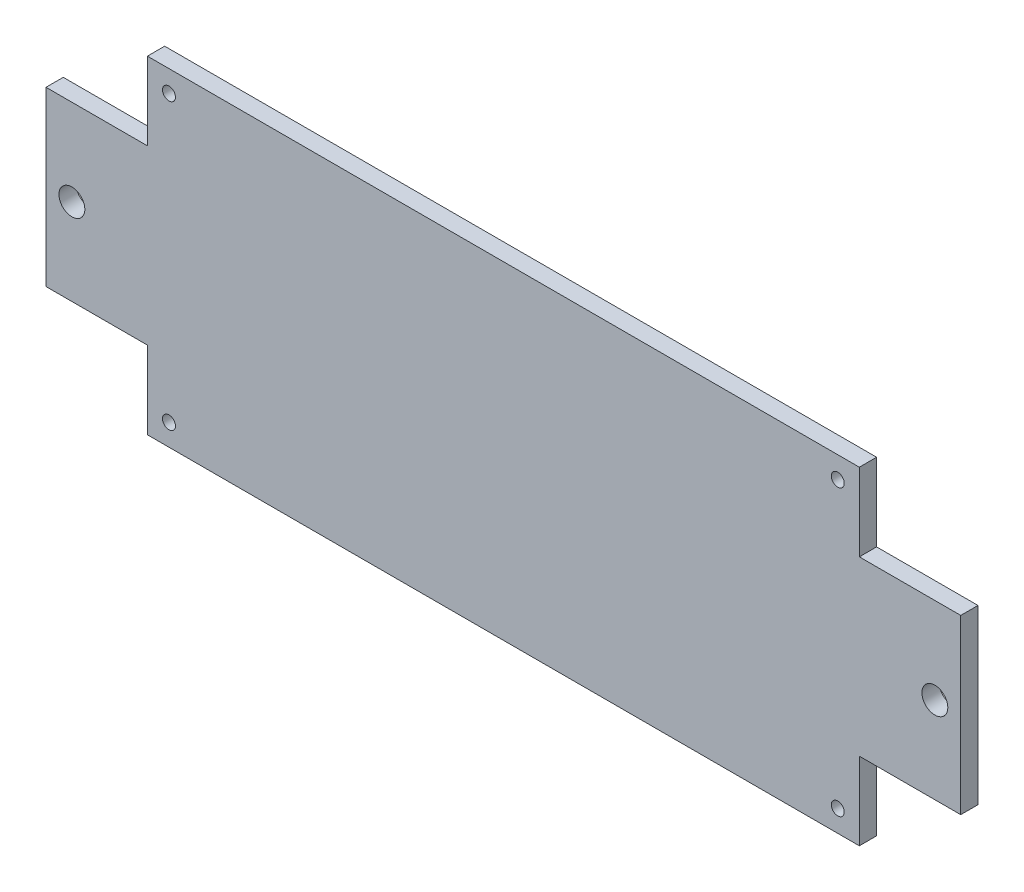
SolidWorks part; units mm, degrees
ref_plane "Front Plane" through (0, 0, 0) normal (0, 0, 1) x (1, 0, 0)
ref_plane "Top Plane" through (0, 0, 0) normal (0, 1, 0) x (1, 0, 0)
ref_plane "Right Plane" through (0, 0, 0) normal (1, 0, 0) x (0, 0, -1)
sketch "Sketch1" plane through (0, 0, 0) normal (0, 0, 1) x (1, 0, 0)
  line L0 (99.0449, 45.8482) -> (99.0449, -30.1518) construction
  line L1 (16.5449, 45.8482) -> (181.5449, 45.8482)
  line L2 (16.5449, 45.8482) -> (16.5449, 27.8482)
  line L3 (16.5449, -30.1518) -> (181.5449, -30.1518)
  line L4 (181.5449, 45.8482) -> (181.5449, 27.8482)
  line L5 (-6.9551, 7.8482) -> (205.0449, 7.8482) construction
  line L6 (181.5449, -12.1518) -> (181.5449, -30.1518)
  line L7 (181.5449, 27.8482) -> (205.0449, 27.8482)
  line L9 (181.5449, -12.1518) -> (205.0449, -12.1518)
  line L10 (205.0449, 27.8482) -> (205.0449, -12.1518)
  line L11 (16.5449, 27.8482) -> (-6.9551, 27.8482)
  line L13 (16.5449, -12.1518) -> (-6.9551, -12.1518)
  line L14 (-6.9551, 27.8482) -> (-6.9551, -12.1518)
  line L15 (16.5449, -12.1518) -> (16.5449, -30.1518)
  circle A0 centre (21.5449, -25.1518) radius 1.5
  circle A1 centre (176.5449, -25.1518) radius 1.5
  circle A2 centre (176.5449, 40.8482) radius 1.5
  circle A3 centre (21.5449, 40.8482) radius 1.5
  circle A4 centre (199.0449, 7.8482) radius 3
  circle A5 centre (-0.9551, 7.8482) radius 3
  point P24 (205.0449, 7.8482)
  point P25 (-6.9551, 7.8482)
  point P27 (99.0449, 7.8482)
  point P29 (99.0449, 7.8482)
  dimension "D1" = 3
  dimension "D5" = 5
  dimension "D8" = 6
  dimension "D9" = 200
  dimension "D2" = 76
  dimension "D3" = 165
  dimension "D4" = 5
  dimension "D6" = 6
  dimension "D7" = 40
extrude "Boss-Extrude1" add sketch "Sketch1" along normal blind 4
